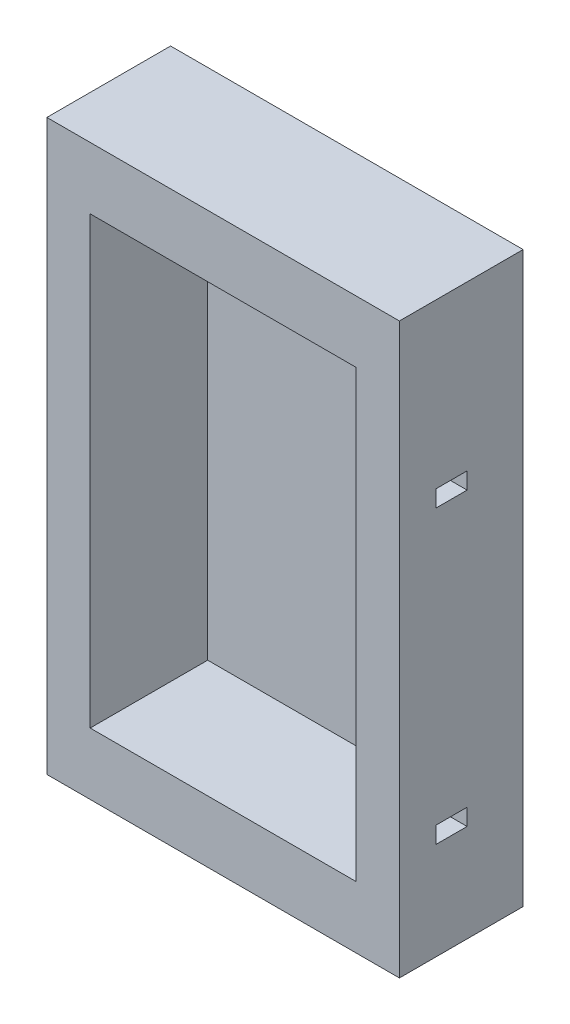
SolidWorks part; units mm, degrees
ref_plane "Front Plane" through (0, 0, 0) normal (0, 0, 1) x (1, 0, 0)
ref_plane "Top Plane" through (0, 0, 0) normal (0, 1, 0) x (1, 0, 0)
ref_plane "Right Plane" through (0, 0, 0) normal (1, 0, 0) x (0, 0, -1)
sketch "Sketch1" plane through (0, 0, 0) normal (0, 0, 1) x (1, 0, 0)
  line L1 (72.39, -116.84) -> (-72.39, -116.84)
  line L2 (72.39, -116.84) -> (72.39, 116.84)
  line L3 (72.39, 116.84) -> (-72.39, 116.84)
  line L4 (-72.39, -116.84) -> (-72.39, 116.84)
  line L5 (72.39, -116.84) -> (-72.39, 116.84) construction
  line L6 (72.39, 116.84) -> (-72.39, -116.84) construction
  point P0 (0, 0)
  dimension "D1" = 144.78
  dimension "D2" = 233.68
extrude "Boss-Extrude1" add sketch "Sketch1" along normal blind 50.8
sketch "Sketch2" plane through (0, 0, 50.8) normal (0, 0, 1) x (1, 0, 0)
  line L1 (54.61, -91.44) -> (-54.61, -91.44)
  line L2 (54.61, -91.44) -> (54.61, 91.44)
  line L3 (54.61, 91.44) -> (-54.61, 91.44)
  line L4 (-54.61, -91.44) -> (-54.61, 91.44)
  line L5 (54.61, -91.44) -> (-54.61, 91.44) construction
  line L6 (54.61, 91.44) -> (-54.61, -91.44) construction
  point P0 (0, 0)
  dimension "D1" = 109.22
  dimension "D2" = 182.88
extrude "Cut-Extrude1" cut sketch "Sketch2" against normal blind 48.26
sketch "Sketch6" plane through (72.39, 0, 0) normal (1, 0, 0) x (0, 0, -1)
  line L0 (-29.35, 46.215) -> (-29.35, -73.415) construction
  line L1 (-35.7, 49.64) -> (-23, 49.64)
  line L2 (-35.7, 49.64) -> (-35.7, 42.79)
  line L3 (-35.7, 42.79) -> (-23, 42.79)
  line L4 (-23, 49.64) -> (-23, 42.79)
  line L5 (-35.7, 49.64) -> (-23, 42.79) construction
  line L6 (-35.7, 42.79) -> (-23, 49.64) construction
  line L12 (-23, -69.99) -> (-35.7, -69.99)
  line L13 (-23, -69.99) -> (-23, -76.84)
  line L14 (-23, -76.84) -> (-35.7, -76.84)
  line L15 (-35.7, -69.99) -> (-35.7, -76.84)
  line L16 (-23, -69.99) -> (-35.7, -76.84) construction
  line L17 (-23, -76.84) -> (-35.7, -69.99) construction
  line L18 (-50.8, 116.84) -> (0, 116.84) construction
  line L19 (0, -116.84) -> (0, 116.84) construction
  line L20 (-50.8, -116.84) -> (0, -116.84) construction
  point P0 (-29.35, 46.215)
  point P5 (-22.8614, -57.2611)
  dimension "D1" = 6.85
  dimension "D2" = 12.7
  dimension "D3" = 12.7
  dimension "D4" = 6.85
  dimension "D5" = 67.2
  dimension "D6" = 23
  dimension "D7" = 40
  dimension "D8" = 23
extrude "Cut-Extrude3" cut sketch "Sketch6" against normal up to next
